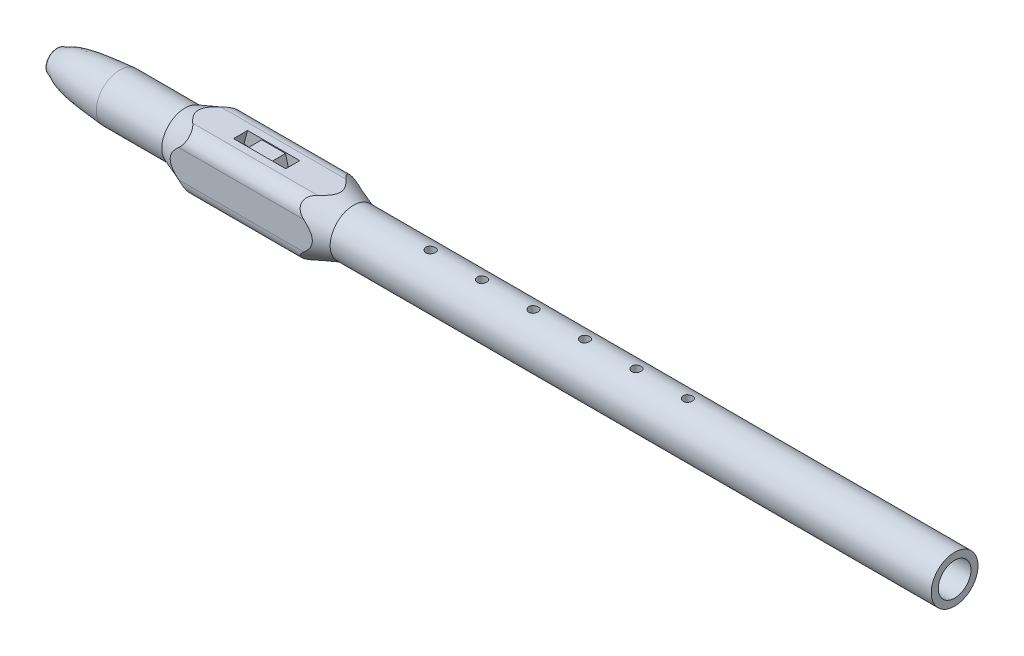
SolidWorks part; units mm, degrees
ref_plane "Front Plane" through (0, 0, 0) normal (0, 0, 1) x (1, 0, 0)
ref_plane "Top Plane" through (0, 0, 0) normal (0, 1, 0) x (1, 0, 0)
ref_plane "Right Plane" through (0, 0, 0) normal (1, 0, 0) x (0, 0, -1)
sketch "Sketch1" plane through (0, 0, 0) normal (1, 0, 0) x (0, 0, -1)
  line L1 (-19.05, 19.05) -> (19.05, 19.05)
  line L2 (-19.05, 19.05) -> (-19.05, -19.05)
  line L3 (-19.05, -19.05) -> (19.05, -19.05)
  line L4 (19.05, 19.05) -> (19.05, -19.05)
  line L5 (-19.05, 19.05) -> (19.05, -19.05) construction
  line L6 (-19.05, -19.05) -> (19.05, 19.05) construction
  point P0 (0, 0)
  dimension "D1" = 38.1
  dimension "D2" = 38.1
extrude "Boss-Extrude1" add sketch "Sketch1" along normal mid plane 609.6
sketch "Sketch2" plane through (0, 0, 0) normal (0, 1, 0) x (1, 0, 0)
  line L0 (-304.8, 0) -> (304.8, 0) construction
  line L1 (-304.8, 19.05) -> (-304.8, -19.05) construction
  line L2 (304.8, 19.05) -> (304.8, -19.05) construction
  line L3 (304.8, 0) -> (-152.4, 0)
  line L4 (-152.4, -11.1125) -> (304.8, -11.1125)
  line L5 (304.8, -11.1125) -> (304.8, 0)
  line L6 (-171.45, 0) -> (-273.05, 0)
  line L7 (-261.9375, -11.1125) -> (-182.5625, -11.1125)
  line L10 (-152.4, -11.1125) -> (-152.4, 0)
  arc A0 (-171.45, 0) -> (-182.5625, -11.1125) centre (-182.5625, 0) cw
  arc A1 (-273.05, 0) -> (-261.9375, -11.1125) centre (-261.9375, 0) ccw
  dimension "D1" = 11.1125
  dimension "D2" = 457.2
  dimension "D3" = 101.6
  dimension "D4" = 31.75
revolve "Cut-Revolve1" cut sketch "Sketch2" angle 360 about L0
sketch "Sketch3" plane through (0, 0, 0) normal (0, 0, 1) x (1, 0, 0)
  line L0 (-304.8, 0) -> (304.8, 0) construction
  line L1 (-304.8, -19.05) -> (-304.8, 19.05) construction
  line L2 (304.8, -11.1125) -> (304.8, 11.1125) construction
  line L3 (304.8, 19.05) -> (304.8, 15.875)
  line L4 (304.8, -19.05) -> (304.8, 19.05) construction
  line L5 (304.8, 15.875) -> (-261.9375, 15.875) construction
  line L6 (-261.9375, 15.875) -> (-299.4785, 13.2679) construction
  line L7 (-299.4785, 13.2679) -> (-300.392, 9.2523) construction
  line L8 (-300.392, 9.2523) -> (-299.32, 8.7003) construction
  line L9 (-299.32, 8.7003) -> (-304.8, 7.62) construction
  line L10 (-304.8, 7.62) -> (-304.8, 19.05)
  line L11 (-304.8, 19.05) -> (-304.8, 56.3779)
  line L12 (-304.8, 56.3779) -> (304.8, 56.3779)
  line L13 (304.8, 56.3779) -> (304.8, 19.05)
  line L14 (-261.9375, 11.1125) -> (-261.9375, 15.875) construction
  line L15 (-160.3375, 15.875) -> (-160.3375, 42.0163) construction
  line L16 (-217.4875, 15.875) -> (-261.9375, 15.875)
  line L17 (-103.1875, 15.875) -> (304.8, 15.875)
  spline S0 degree 4 poles (-261.9375, 15.875) (-299.4785, 13.2679) (-300.392, 9.2523) (-299.32, 8.7003) (-304.8, 7.62) knots 0 0 0 0 0 1 1 1 1 1
  spline S1 degree 2 poles (-103.1875, 15.875) (-131.4574, 25.4177) (-160.3375, 42.0163) knots 0 0 0 0.605945 0.605945 0.605945
  spline S2 degree 2 poles (-217.4875, 15.875) (-189.2176, 25.4177) (-160.3375, 42.0163) knots 0 0 0 0.605945 0.605945 0.605945
  dimension "D1" = 15.875
  dimension "D2" = 7.62
  dimension "D3" = 57.15
  dimension "D4" = 44.45
revolve "Cut-Revolve2" cut sketch "Sketch3" angle 360 about L0
sketch "Sketch4" plane through (-304.8, 0, 0) normal (-1, 0, 0) x (0, 0, 1)
  circle A0 centre (0, 0) radius 3.175
  dimension "D1" = 6.35
extrude "Cut-Extrude1" cut sketch "Sketch4" against normal blind 50.8
fillet "Fillet1" radius 1.27 1 edges at (-304.8, -7.62, 0)
sketch "Sketch5" plane through (0, 0, 0) normal (0, 1, 0) x (1, 0, 0)
  line L0 (304.8, 0) -> (123.825, 0) construction
  line L2 (123.825, 0) -> (88.9, 0) construction
  line L3 (88.9, 0) -> (53.975, 0) construction
  line L4 (53.975, 0) -> (19.05, 0) construction
  line L5 (19.05, 0) -> (-15.875, 0) construction
  line L6 (-15.875, 0) -> (-50.8, 0) construction
  line L7 (-50.8, 0) -> (-304.8, 0) construction
  line L8 (-304.8, 6.5886) -> (-304.8, -6.5886) construction
  line L9 (-152.4, -11.1125) -> (-152.4, 11.1125) construction
  circle A0 centre (-50.8, 0) radius 3.175
  circle A1 centre (-15.875, 0) radius 3.175
  circle A2 centre (19.05, 0) radius 3.175
  circle A3 centre (53.975, 0) radius 3.175
  circle A4 centre (88.9, 0) radius 3.175
  circle A5 centre (123.825, 0) radius 3.175
  dimension "D1" = 6.35
  dimension "D2" = 34.925
  dimension "D3" = 101.6
extrude "Cut-Extrude2" cut sketch "Sketch5" along normal through all
ref_plane "Plane1" through (0, 15.875, 0) normal (0, 1, 0) x (1, 0, 0)
sketch "Sketch7" plane through (0, 0, 0) normal (0, 0, 1) x (1, 0, 0)
  line L0 (-152.4, 0) -> (-162.1459, 0) construction
  line L1 (-152.4, -11.1125) -> (-152.4, 11.1125) construction
  line L2 (-162.1459, 0) -> (-162.1459, 37.5745) construction
  line L3 (-177.7775, 26.8688) -> (-184.4276, 2.0505)
  line L4 (-177.7775, 26.8688) -> (-168.5771, 24.4036)
  line L5 (-184.4276, 2.0505) -> (-175.2271, -0.4147)
  line L6 (-168.5771, 24.4036) -> (-175.2271, -0.4147)
  line L7 (-177.7775, 26.8688) -> (-175.2271, -0.4147) construction
  line L8 (-184.4276, 2.0505) -> (-168.5771, 24.4036) construction
  line L9 (-182.5625, 11.1125) -> (-182.5625, -11.1125) construction
  line L10 (-146.5143, 26.8688) -> (-155.7147, 24.4036)
  line L11 (-146.5143, 26.8688) -> (-139.8642, 2.0505)
  line L12 (-139.8642, 2.0505) -> (-149.0647, -0.4147)
  line L13 (-155.7147, 24.4036) -> (-149.0647, -0.4147)
  point P5 (-182.5625, 9.0111)
  point P7 (-176.5023, 13.227)
  point P8 (-182.5625, 9.0111)
  dimension "D1" = 9.525
  dimension "D2" = 75
extrude "Cut-Extrude4" cut sketch "Sketch7" against normal mid plane 9.525
sketch "Sketch8" plane through (0, 19.05, 0) normal (0, 1, 0) x (1, 0, 0)
  line L0 (-154.2803, -4.7625) -> (-144.4193, -4.7625) construction
  line L1 (-172.726, 4.7625) -> (-153.198, 4.7625)
  line L2 (-172.726, 4.7625) -> (-172.726, -4.7625)
  line L3 (-172.726, -4.7625) -> (-153.198, -4.7625)
  line L4 (-153.198, 4.7625) -> (-153.198, -4.7625)
  line L5 (-179.8726, 4.7625) -> (-170.0116, 4.7625) construction
extrude "Cut-Extrude5" cut sketch "Sketch8" against normal blind 0.635
fillet "Fillet2" radius 9.525 4 edges at (-160.3375, -19.05, -19.05) (-160.3375, -19.05, 19.05) (-160.3375, 19.05, -19.05) (-160.3375, 19.05, 19.05)
